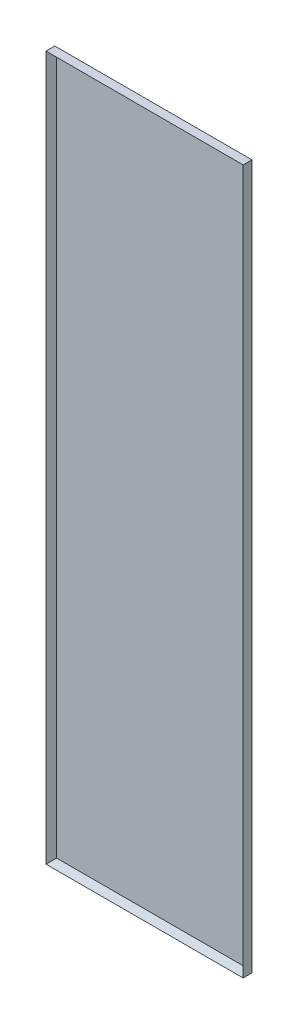
SolidWorks part; units mm, degrees
ref_plane "Front Plane" through (0, 0, 0) normal (0, 0, 1) x (1, 0, 0)
ref_plane "Top Plane" through (0, 0, 0) normal (0, 1, 0) x (1, 0, 0)
ref_plane "Right Plane" through (0, 0, 0) normal (1, 0, 0) x (0, 0, -1)
sketch "Sketch2" plane through (0, 0, 0) normal (0, 0, 1) x (1, 0, 0)
  line L1 (0, 0) -> (560, 0)
  line L2 (0, 0) -> (0, 2000)
  line L3 (0, 2000) -> (560, 2000)
  line L4 (560, 0) -> (560, 2000)
  dimension "D1" = 2000
  dimension "D2" = 560
extrude "Boss-Extrude1" add sketch "Sketch2" along normal blind 25
sketch "Sketch4" plane through (0, 0, 25) normal (0, 0, 1) x (1, 0, 0)
  line L4 (0, 2000) -> (0, 0)
  line L5 (0, 0) -> (560, 0)
  line L6 (560, 0) -> (560, 2000)
  line L7 (560, 2000) -> (0, 2000)
  line L8 (0, 2000) -> (0, 0)
  line L9 (0, 0) -> (560, 0)
  line L10 (560, 0) -> (560, 2000)
  line L11 (560, 2000) -> (0, 2000)
  dimension "D1" = 0
extrude "Cut-Extrude1" cut sketch "Sketch4" against normal blind 15 draft 45
